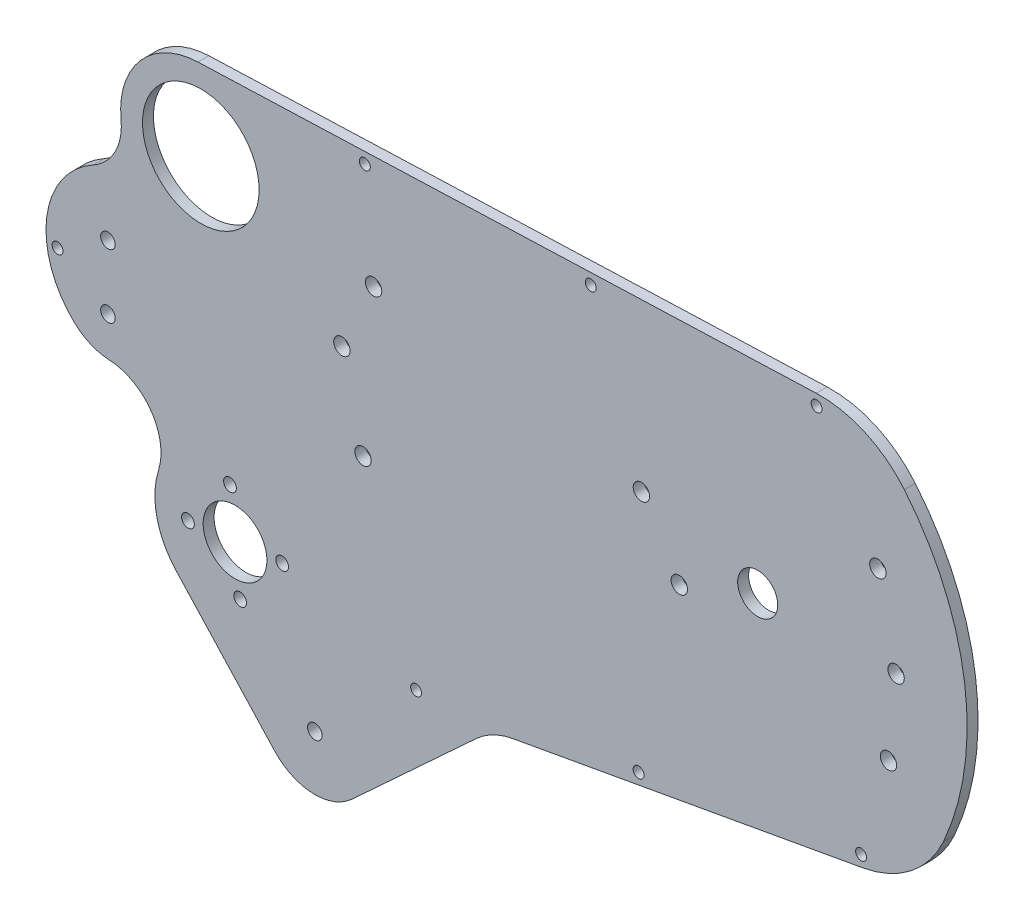
SolidWorks part; units mm, degrees
ref_plane "Front Plane" through (0, 0, 0) normal (0, 0, 1) x (1, 0, 0)
ref_plane "Top Plane" through (0, 0, 0) normal (0, 1, 0) x (1, 0, 0)
ref_plane "Right Plane" through (0, 0, 0) normal (1, 0, 0) x (0, 0, -1)
sketch "Sketch1" plane through (0, 0, 0) normal (0, 0, 1) x (1, 0, 0)
  line L0 (86.8854, -33.5) -> (-137.2004, -33.5) construction
  line L1 (-111.886, 49.4802) -> (83.0489, 41.2139) construction
  line L2 (-115.2069, 49.6211) -> (-101.035, -81.6153) construction
  line L3 (-97.8208, -80.7688) -> (92.1699, -30.731) construction
  line L4 (78.7977, 41.3942) -> (86.7407, -32.1609) construction
  line L5 (-108.121, -15.9971) -> (82.7692, 4.6166) construction
  line L6 (91, -33.5) -> (-88.5, -33.5) construction
  line L7 (-97.4673, 5.5) -> (-155.3054, 5.5) construction
  line L8 (-138.3, -14) -> (-155.3054, -14) construction
  line L9 (-138.3, 5.5) -> (-138.3, -33.5) construction
  line L10 (-155.3054, 5.5) -> (-155.3054, -33.5) construction
  line L11 (40.0178, 33.5) -> (40.0178, -33.5) construction
  line L12 (-101.0559, -81.4218) -> (-90.5433, -79.5278)
  line L13 (-91.5, 33.5) -> (88, 33.5) construction
  line L14 (-68.3, -21.5) -> (-107.0746, -25.6872) construction
  line L15 (-138.3, -5.25) -> (-81.5148, -93.5701) construction
  line L17 (-119.5948, -74.4106) -> (-92.5405, -103.7404)
  line L18 (-71.3446, -104.5958) -> (-37.2211, -73.1197)
  line L19 (-27.1401, -68.1042) -> (68.9251, -50.7959)
  line L20 (-117.3596, 49.3503) -> (56.0883, 55.6165)
  circle A0 centre (40.0178, 0) radius 5.5
  circle A1 centre (-112.8181, 27.5) radius 13 construction
  circle A2 centre (-103.4238, -59.4942) radius 13 construction
  arc A3 (-91.5, 33.5) -> (-88.5, -33.5) centre (-18.0922, 3.2198) ccw construction
  circle A4 centre (-68.3, -21.5) radius 2.25
  circle A6 centre (-138.3, -5.25) radius 2
  circle A7 centre (-138.3, -22.75) radius 2
  arc A8 (-142.3827, 10.6321) -> (-147.5429, -29.3643) centre (-130.3054, -11.2571) ccw
  arc A9 (-147.5429, -29.3643) -> (-137.2004, -33.5) centre (-137.2004, -18.5) ccw
  circle A10 centre (-112.8181, 27.5) radius 22
  arc A11 (68.9251, -50.7959) -> (91, -33.5) centre (63.6055, -21.2712) ccw
  circle A12 centre (-103.4238, -59.4942) radius 22
  arc A13 (91, -33.5) -> (80.2612, 44.7896) centre (22.6589, -2.9929) ccw
  arc A14 (91, -33.5) -> (88, 33.5) centre (22.6589, -2.9929) ccw construction
  arc A17 (-124.4228, -52.9336) -> (-137.9704, -33.4802) centre (-138.7403, -48.4604) ccw
  arc A18 (-142.3827, 10.6321) -> (-134.7058, 25.2795) centre (-149.6292, 23.7656) ccw
  circle A19 centre (-74.1, 1.7) radius 2.25
  circle A20 centre (-65.4, 20.2) radius 2.25
  circle A21 centre (8.1, 8.2) radius 2.25
  circle A23 centre (18.5, -8.7) radius 2.25
  circle A25 centre (78, -0.1) radius 2.25
  circle A26 centre (75.9, -21.8) radius 2.25
  circle A27 centre (73, 22.4) radius 2.25
  arc A28 (80.2612, 44.7896) -> (56.0883, 55.6165) centre (57.1714, 25.636) ccw
  circle A30 centre (-81.5148, -93.5701) radius 2
  circle A36 centre (-114.2138, 40.4249) radius 1.75
  circle A37 centre (-99.8933, 28.8957) radius 1.75
  circle A38 centre (-111.4224, 14.5751) radius 1.75
  circle A39 centre (-125.743, 26.1043) radius 1.75
  circle A40 centre (-104.8196, -46.5694) radius 1.75
  circle A41 centre (-90.499, -58.0985) radius 1.75
  circle A42 centre (-102.0281, -72.4191) radius 1.75
  circle A43 centre (-116.3487, -60.89) radius 1.75
  circle A44 centre (40.0178, 0) radius 35 construction
  circle A45 centre (40.0178, 0) radius 43
  circle A49 centre (-103.4238, -59.4942) radius 16
  circle A50 centre (-112.8181, 27.5) radius 16
  circle A51 centre (-112.8181, 27.5) radius 8.75
  circle A52 centre (-103.4238, -59.4942) radius 8.75
  arc A53 (91, -33.5) -> (88, 33.5) centre (22.6589, -2.9929) ccw construction
  arc A54 (-92.5405, -103.7404) -> (-71.3446, -104.5958) centre (-81.5148, -93.5701) ccw
  arc A55 (-27.1401, -68.1042) -> (-37.2211, -73.1197) centre (-23.5699, -87.9191) ccw
  circle A56 centre (-68.3, -21.5) radius 2.25 construction
  circle A57 centre (-74.1, 1.7) radius 2.25 construction
  circle A58 centre (-65.4, 20.2) radius 2.25 construction
  circle A59 centre (18.5, -8.7) radius 2.25 construction
  circle A60 centre (8.1, 8.2) radius 2.25 construction
  circle A61 centre (75.9, -21.8) radius 2.25 construction
  circle A62 centre (78, -0.1) radius 2.25 construction
  circle A63 centre (73, 22.4) radius 2.25 construction
  point P52 (82.7692, 4.6166)
  point P109 (-112.8181, 27.5)
  point P118 (-103.4238, -59.4942)
  dimension "D5" = 4
  dimension "D6" = 25
  dimension "D9" = 15
  dimension "D13" = 30
  dimension "D14" = 26
  dimension "D11" = 44
  dimension "D15" = 3.5
  dimension "D12" = 70
  dimension "D19" = 11
  dimension "D20" = 17.5
  dimension "D22" = 32
  dimension "D24" = 4
  dimension "D26" = 55
  dimension "D2" = 39
  dimension "D3" = 70
  dimension "D4" = 17.5
  dimension "D7" = 14
  dimension "D8" = 10
  dimension "D10" = 87.5
  dimension "D21" = 192
  dimension "D23" = 39
  dimension "D25" = 105
  dimension "D18" = 8
  dimension "D16" = 4
  dimension "D17" = 4
extrude "Boss-Extrude1" add sketch "Sketch1" along normal blind 3
sketch "Sketch2" plane through (0, 0, 3) normal (0, 0, 1) x (1, 0, 0)
  line L0 (68.3931, -47.8434) -> (7.3358, -58.8443) construction
  line L1 (-138.3, -5.25) -> (-138.3, -22.75) construction
  line L2 (7.3358, -58.8443) -> (-53.7216, -69.8452) construction
  line L7 (56.1966, 52.6184) -> (-113.5041, 46.4876)
  line L8 (56.1966, 52.6184) -> (-113.5041, 46.4876)
  line L9 (-67.8034, 48.1386) -> (-5.8034, 50.3785) construction
  line L10 (-5.8034, 50.3785) -> (56.1966, 52.6184) construction
  line L13 (-117.3897, -72.3766) -> (-90.3354, -101.7064)
  line L14 (-73.3786, -102.3907) -> (-39.2552, -70.9146)
  line L15 (-27.672, -65.1517) -> (68.3931, -47.8434)
  line L17 (-117.3897, -72.3766) -> (-90.3354, -101.7064) construction
  line L18 (-73.3786, -102.3907) -> (-39.2552, -70.9146) construction
  line L19 (-110.3186, -80.0424) -> (68.3931, -47.8434) construction
  circle A0 centre (7.3358, -58.8443) radius 1.5
  circle A2 centre (-53.7216, -69.8452) radius 1.5
  arc A14 (77.9522, 42.8742) -> (56.1966, 52.6184) centre (57.1714, 25.636) ccw
  arc A15 (77.9522, 42.8742) -> (56.1966, 52.6184) centre (57.1714, 25.636) ccw
  arc A16 (68.3931, -47.8434) -> (88.2606, -32.2771) centre (63.6055, -21.2712) ccw
  arc A17 (-114.7845, -75.2008) -> (-103.8362, -78.8745) centre (-105.964, -67.0646) ccw construction
  circle A21 centre (68.3931, -47.8434) radius 1.5
  circle A23 centre (56.1966, 52.6184) radius 1.5
  circle A24 centre (-5.8034, 50.3785) radius 1.5
  circle A27 centre (-67.8034, 48.1386) radius 1.5
  arc A28 (-113.5041, 46.4876) -> (-131.7211, 25.5823) centre (-112.8181, 27.5) ccw
  arc A29 (-140.9335, 8.0053) -> (-131.7211, 25.5823) centre (-149.6292, 23.7656) ccw
  arc A30 (-140.9335, 8.0053) -> (-145.4744, -27.1914) centre (-130.3054, -11.2571) ccw
  arc A31 (-145.4744, -27.1914) -> (-137.8164, -30.4842) centre (-137.2004, -18.5) ccw
  arc A32 (-121.5593, -53.8282) -> (-137.8164, -30.4842) centre (-138.7403, -48.4604) ccw
  arc A33 (-121.5593, -53.8282) -> (-117.3897, -72.3766) centre (-103.4238, -59.4942) ccw
  arc A34 (-90.3354, -101.7064) -> (-73.3786, -102.3907) centre (-81.5148, -93.5701) ccw
  arc A35 (-27.672, -65.1517) -> (-39.2552, -70.9146) centre (-23.5699, -87.9191) ccw
  arc A36 (88.2606, -32.2771) -> (77.9522, 42.8742) centre (22.6589, -2.9929) ccw
  arc A37 (-113.5041, 46.4876) -> (-131.7211, 25.5823) centre (-112.8181, 27.5) ccw construction
  arc A38 (-140.9335, 8.0053) -> (-131.7211, 25.5823) centre (-149.6292, 23.7656) ccw construction
  arc A39 (-140.9335, 8.0053) -> (-145.4744, -27.1914) centre (-130.3054, -11.2571) ccw construction
  arc A40 (-145.4744, -27.1914) -> (-137.8164, -30.4842) centre (-137.2004, -18.5) ccw construction
  arc A41 (-121.5593, -53.8282) -> (-137.8164, -30.4842) centre (-138.7403, -48.4604) ccw construction
  arc A42 (-121.5593, -53.8282) -> (-117.3897, -72.3766) centre (-103.4238, -59.4942) ccw construction
  arc A43 (-90.3354, -101.7064) -> (-73.3786, -102.3907) centre (-81.5148, -93.5701) ccw construction
  arc A44 (-27.672, -65.1517) -> (-39.2552, -70.9146) centre (-23.5699, -87.9191) ccw construction
  arc A45 (88.2606, -32.2771) -> (77.9522, 42.8742) centre (22.6589, -2.9929) ccw construction
  circle A47 centre (-152.1337, -14) radius 1.5
  arc A51 (68.3931, -47.8434) -> (88.2606, -32.2771) centre (63.6055, -21.2712) ccw
  point P2 (-138.3, -14)
  dimension "D4" = 3
  dimension "D2" = 62
  dimension "D1" = 3
extrude "Cut-Extrude1" cut sketch "Sketch2" against normal through all
